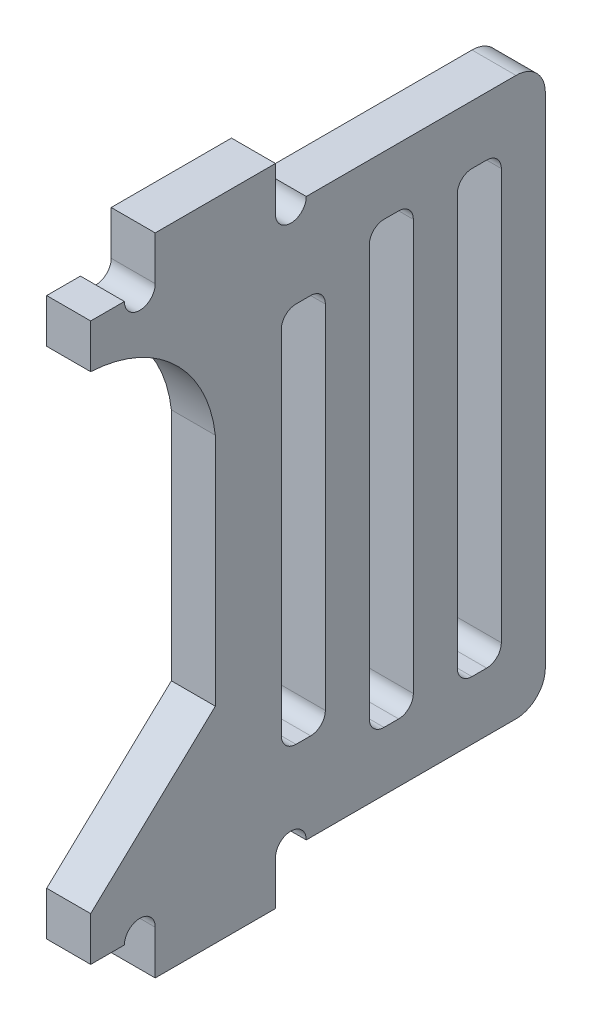
SolidWorks part; units mm, degrees
material "Thornel Mat VMA"
ref_plane "前视基准面" through (0, 0, 0) normal (0, 0, 1) x (1, 0, 0)
ref_plane "上视基准面" through (0, 0, 0) normal (0, 1, 0) x (1, 0, 0)
ref_plane "右视基准面" through (0, 0, 0) normal (1, 0, 0) x (0, 0, -1)
sketch "草图1" plane through (0, 0, 0) normal (1, 0, 0) x (0, 0, -1)
  line L0 (-4.1, 19) -> (-4.1, 22)
  line L1 (8.5, -19) -> (4.1, -19)
  line L2 (8.5, -19) -> (8.5, 19)
  line L3 (8.5, 19) -> (4.1, 19)
  line L4 (-8.5, -19) -> (-8.5, 19)
  line L5 (8.5, -19) -> (-8.5, 19) construction
  line L6 (8.5, 19) -> (-8.5, -19) construction
  line L7 (-4.1, 22) -> (4.1, 22)
  line L8 (4.1, 22) -> (4.1, 19)
  line L9 (0, 22) -> (0, 0) construction
  line L10 (0, 0) -> (9.1787, 0) construction
  line L11 (4.1, -22) -> (4.1, -19)
  line L12 (-4.1, -22) -> (4.1, -22)
  line L13 (-4.1, -19) -> (-4.1, -22)
  line L14 (-4.1, 19) -> (-8.5, 19)
  line L15 (-4.1, -19) -> (-8.5, -19)
  circle A0 centre (5.15, 19) radius 1.05
  circle A1 centre (-5.15, 19) radius 1.05
  circle A2 centre (5.15, -19) radius 1.05
  circle A3 centre (-5.15, -19) radius 1.05
  dimension "D3" = 2.1
  dimension "D1" = 17
  dimension "D2" = 8.2
  dimension "D4" = 44
  dimension "D5" = 3
extrude "凸台-拉伸1" add sketch "草图1" along normal blind 3
sketch "草图4" plane through (3, 0, 0) normal (1, 0, 0) x (0, 0, -1)
  line L0 (8.5, -19) -> (8.5, 19) construction
  line L1 (8.5, -19) -> (22.5, -19)
  line L2 (8.5, -19) -> (8.5, 19)
  line L3 (8.5, 19) -> (22.5, 19)
  line L4 (22.5, -19) -> (22.5, 19)
  line L6 (8.5, 0) -> (22.5, 0) construction
  line L7 (10.5, -15) -> (13.5, -15)
  line L12 (16.5, -15) -> (19.5, -15)
  line L13 (19.5, 15) -> (19.5, -15)
  line L14 (13.5, 15) -> (13.5, -15)
  line L15 (10.5, 15) -> (13.5, 15)
  line L16 (10.5, 15) -> (10.5, -15)
  line L17 (16.5, 15) -> (19.5, 15)
  line L22 (16.5, 15) -> (16.5, -15)
  line L31 (28.5, -15) -> (31.5, -15) [skipped]
  line L32 (28.5, 15) -> (31.5, 15) [skipped]
  line L33 (28.5, 15) -> (28.5, -15) [skipped]
  line L34 (31.5, 15) -> (31.5, -15) [skipped]
  line L35 (22.5, -15) -> (25.5, -15) [skipped]
  line L36 (22.5, 15) -> (25.5, 15) [skipped]
  line L37 (22.5, 15) -> (22.5, -15) [skipped]
  line L38 (25.5, 15) -> (25.5, -15) [skipped]
  dimension "D1" = 3
  dimension "D2" = 3
  dimension "D3" = 2
  dimension "D4" = 4
  dimension "D5" = 4
  dimension "D6" = 6
extrude "凸台-拉伸2" add sketch "草图4" against normal up to surface (3 mm away) up to face at (0, 0, 0)
fillet "圆角1" radius 2 2 edges at (1.5, 19, -22.5) (1.5, -19, -22.5)
sketch "草图5" plane through (3, 0, 0) normal (1, 0, 0) x (0, 0, -1)
  line L0 (-8.5, -16) -> (0, -8)
  line L1 (-6.2, -19) -> (-8.5, -19) construction
  line L2 (-8.5, 16) -> (-8.5, -16)
  line L3 (0, 0) -> (-15.741, 0) construction
  line L4 (-8.5, -19) -> (-8.5, 19) construction
  line L5 (0, -8) -> (0, 8)
  line L7 (-8.5, 16) -> (0, 8) construction
  line L8 (4.5, 13) -> (4.5, -13)
  line L9 (4.5, -13) -> (7.5, -13)
  line L10 (7.5, -13) -> (7.5, 13)
  line L11 (7.5, 13) -> (4.5, 13)
  line L14 (10.5, 15) -> (10.5, -15) construction
  line L15 (20.5, 19) -> (6.2, 19) construction
  arc A2 (0, 8) -> (-8.5, 16) centre (-8.9455, 7.011) ccw
  dimension "D2" = 3
  dimension "D4" = 18
  dimension "D1" = 16
  dimension "D3" = 3
  dimension "D5" = 3
  dimension "D6" = 3
  dimension "D7" = 6
extrude "切除-拉伸1" cut sketch "草图5" against normal blind 10
fillet "圆角2" radius 1 12 edges at (1.5, -15, -16.5) (1.5, 15, -16.5) (1.5, 15, -19.5) (1.5, -15, -19.5) (1.5, -15, -10.5) (1.5, 15, -10.5) (1.5, 15, -13.5) (1.5, -15, -13.5) (1.5, -13, -7.5) (1.5, -13, -4.5) (1.5, 13, -7.5) (1.5, 13, -4.5)
